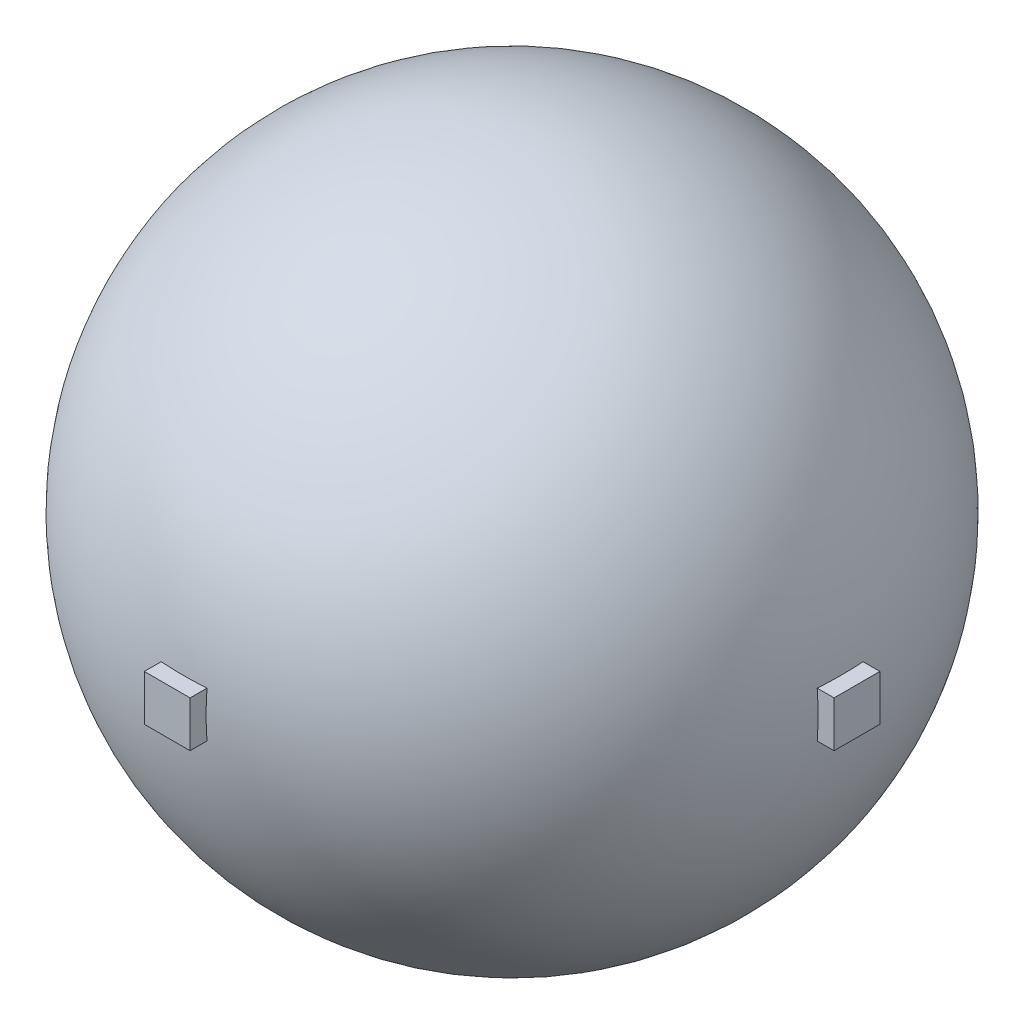
SolidWorks part; units mm, degrees
material "6061 Alloy"
ref_plane "Front Plane" through (0, 0, 0) normal (0, 0, 1) x (1, 0, 0)
ref_plane "Top Plane" through (0, 0, 0) normal (0, 1, 0) x (1, 0, 0)
ref_plane "Right Plane" through (0, 0, 0) normal (1, 0, 0) x (0, 0, -1)
sketch "Sketch1" plane through (0, 0, 0) normal (0, 1, 0) x (1, 0, 0)
  line L0 (0, 0) -> (341.122, 0) construction
  line L1 (-274.32, 0) -> (274.32, 0)
  arc A0 (274.32, 0) -> (-274.32, 0) centre (0, 0) ccw
  point P7 (341.122, 0)
  dimension "D1" = 548.64
revolve "Revolve6" add sketch "Sketch1" angle 360 about L1
shell "Shell1" thickness 3.175
sketch "Sketch2" plane through (0, 0, 0) normal (0, 1, 0) x (1, 0, 0)
  line L0 (-367.919, 0) -> (367.919, 0)
  line L1 (367.919, -152.4) -> (367.919, 152.4)
  line L2 (152.3949, -367.9211) -> (367.9211, -152.3949)
  line L3 (-152.4, -367.919) -> (152.4, -367.919)
  line L4 (-367.9211, -152.3949) -> (-152.3949, -367.9211)
  line L5 (-367.919, 152.4) -> (-367.919, -152.4)
  line L6 (-152.3949, 367.9211) -> (-367.9211, 152.3949)
  line L7 (152.4, 367.919) -> (-152.4, 367.919)
  line L8 (367.9211, 152.3949) -> (152.3949, 367.9211)
  line L9 (141.876, 342.519) -> (-141.876, 342.519)
  line L10 (-141.876, 342.519) -> (-342.519, 141.876)
  line L11 (-342.519, 141.876) -> (-342.519, -141.876)
  line L12 (-342.519, -141.876) -> (-141.876, -342.519)
  line L13 (-141.876, -342.519) -> (141.876, -342.519)
  line L14 (141.876, -342.519) -> (342.519, -141.876)
  line L15 (342.519, -141.876) -> (342.519, 141.876)
  line L16 (342.519, 141.876) -> (141.876, 342.519)
  line L17 (-342.519, 152.4) -> (-342.519, -152.4) construction
  line L18 (-134.4344, 349.9606) -> (-349.9606, 134.4344) construction
  line L19 (152.4, 342.519) -> (-152.4, 342.519) construction
  line L20 (349.9606, 134.4344) -> (134.4344, 349.9606) construction
  line L21 (342.519, -152.4) -> (342.519, 152.4) construction
  line L22 (134.4344, -349.9606) -> (349.9606, -134.4344) construction
  line L23 (-152.4, -342.519) -> (152.4, -342.519) construction
  line L24 (-349.9606, -134.4344) -> (-134.4344, -349.9606) construction
  point P4 (0, 0)
  point P7 (367.919, 0)
  dimension "D1" = 735.838
  dimension "D2" = 304.8
  dimension "D4" = 25.4
  dimension "D3" = 8
sketch "Sketch5" plane through (0, 0, 0) normal (0, 0, 1) x (1, 0, 0)
  line L0 (0, 0) -> (0, -338.0546)
ref_plane "Plane3" through (0, 0, 287.02) normal (0, 0, 1) x (1, 0, 0)
sketch "Sketch4" plane through (0, 0, 287.02) normal (0, 0, 1) x (1, 0, 0)
  line L1 (-19.05, -19.05) -> (19.05, -19.05)
  line L2 (-19.05, -19.05) -> (-19.05, 19.05)
  line L3 (-19.05, 19.05) -> (19.05, 19.05)
  line L4 (19.05, -19.05) -> (19.05, 19.05)
  line L5 (-19.05, -19.05) -> (19.05, 19.05) construction
  line L6 (-19.05, 19.05) -> (19.05, -19.05) construction
  point P0 (0, 0)
  dimension "D1" = 38.1
  dimension "D2" = 38.1
extrude "Boss-Extrude2" add sketch "Sketch4" against normal up to surface (14.0261 mm away)
pattern_circular "CirPattern2" count 4 over 360 about axis through (0, 0, 0) along (0, 1, 0) of "Boss-Extrude2"
